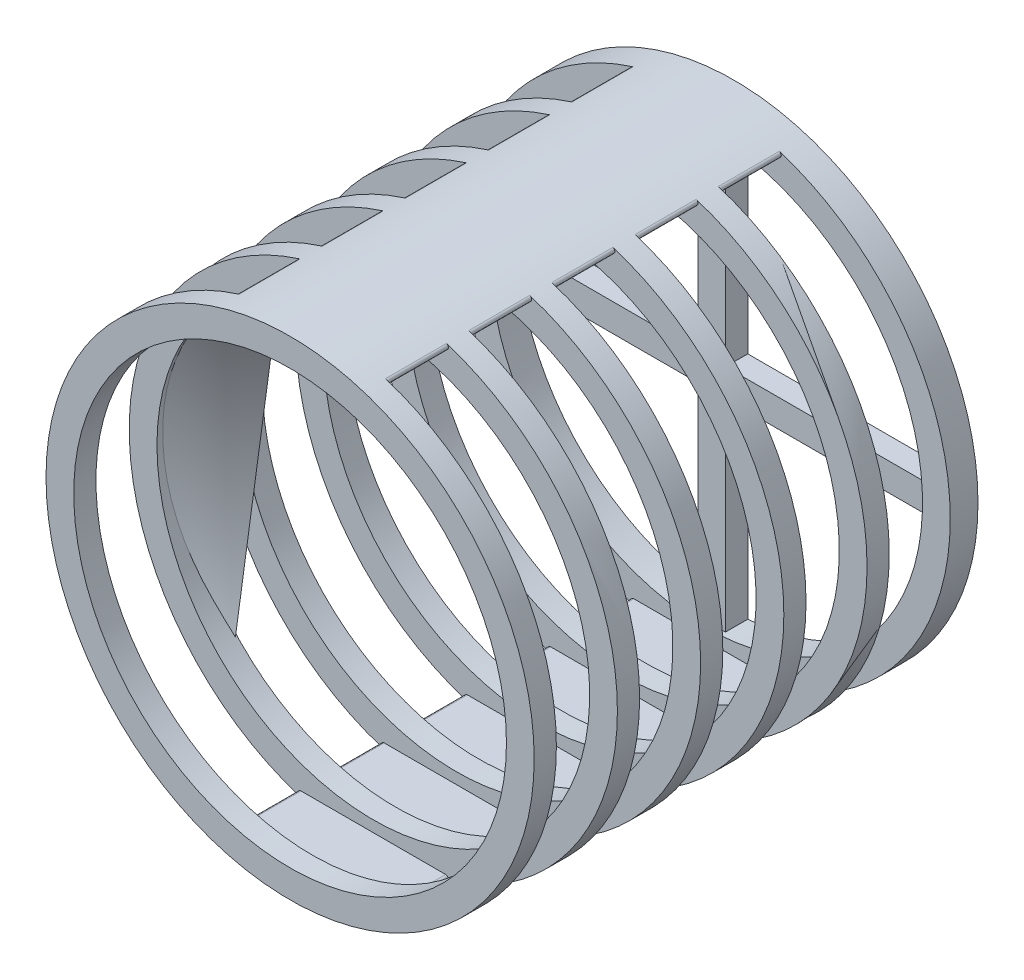
SolidWorks part; units mm, degrees
ref_plane "Plan de face" through (0, 0, 0) normal (0, 0, 1) x (1, 0, 0)
ref_plane "Plan de dessus" through (0, 0, 0) normal (0, 1, 0) x (1, 0, 0)
ref_plane "Plan de droite" through (0, 0, 0) normal (1, 0, 0) x (0, 0, -1)
sketch "Esquisse2" plane through (0, 0, 0) normal (0, 0, 1) x (1, 0, 0)
  circle A0 centre (0, 0) radius 44
  circle A1 centre (0, 0) radius 39
  dimension "D1" = 78
  dimension "D2" = 5
extrude "Boss.-Extru.1" add sketch "Esquisse2" along normal blind 80
sketch "Esquisse3" plane through (0, 0, 0) normal (0, 0, -1) x (-1, 0, 0)
  line L0 (-2.5, 2.5) -> (-42, 2.5)
  line L1 (-42, 2.5) -> (-42, -2.5)
  line L2 (-42, 0) -> (0, 0) construction
  line L3 (-2.5, -2.5) -> (-42, -2.5)
  line L4 (2.5, 2.5) -> (2.5, 42)
  line L5 (2.5, 42) -> (-2.5, 42)
  line L6 (-2.5, 2.5) -> (-2.5, 42)
  line L7 (0, 42) -> (0, 0) construction
  line L8 (2.5, -2.5) -> (42, -2.5)
  line L9 (42, -2.5) -> (42, 2.5)
  line L10 (2.5, 2.5) -> (42, 2.5)
  line L11 (42, 0) -> (0, 0) construction
  line L12 (-2.5, -2.5) -> (-2.5, -42)
  line L13 (-2.5, -42) -> (2.5, -42)
  line L14 (2.5, -2.5) -> (2.5, -42)
  line L15 (0, -42) -> (0, 0) construction
  circle A1 centre (0, 0) radius 44 construction
  point P9 (0, 0)
  point P10 (-2.5, 4.4124)
  point P27 (0, 0)
  dimension "D1" = 5
  dimension "D2" = 42
  dimension "D3" = 4
extrude "Boss.-Extru.2" add sketch "Esquisse3" against normal blind 4
sketch "Esquisse4" plane through (0, 0, 0) normal (1, 0, 0) x (0, 0, -1)
  line L0 (0, -44) -> (0, 44) construction
  line L1 (-16, -41) -> (-5, -41)
  line L2 (-16, -41) -> (-16, 41)
  line L3 (-16, 41) -> (-5, 41)
  line L4 (-5, -41) -> (-5, 41)
  line L5 (-5, 0) -> (0, 0) construction
  line L6 (-31, -41) -> (-20, -41)
  line L7 (-31, -41) -> (-31, 41)
  line L8 (-31, 41) -> (-20, 41)
  line L9 (-20, -41) -> (-20, 41)
  line L10 (-46, -41) -> (-35, -41)
  line L11 (-46, -41) -> (-46, 41)
  line L12 (-46, 41) -> (-35, 41)
  line L13 (-35, -41) -> (-35, 41)
  line L14 (-61, -41) -> (-50, -41)
  line L15 (-61, -41) -> (-61, 41)
  line L16 (-61, 41) -> (-50, 41)
  line L17 (-50, -41) -> (-50, 41)
  line L18 (-76, -41) -> (-65, -41)
  line L19 (-76, -41) -> (-76, 41)
  line L20 (-76, 41) -> (-65, 41)
  line L21 (-65, -41) -> (-65, 41)
  point P9 (-18, -41)
  dimension "D1" = 5
  dimension "D2" = 11
  dimension "D3" = 82
  dimension "D5" = 15
  dimension "D4" = 5
extrude "Enlèv. mat.-Extru.1" cut sketch "Esquisse4" against normal through all both and the other way through all
fillet "Congé1" radius 0.5 20 edges at (-15.9687, 41, 70.5) (15.9687, 41, 70.5) (-15.9687, 41, 55.5) (15.9687, 41, 55.5) (-15.9687, 41, 40.5) (15.9687, 41, 40.5) (-15.9687, 41, 25.5) (15.9687, 41, 25.5) (-15.9687, 41, 10.5) (15.9687, 41, 10.5) (-15.9687, -41, 70.5) (15.9687, -41, 70.5) (-15.9687, -41, 55.5) (15.9687, -41, 55.5) (-15.9687, -41, 40.5) (15.9687, -41, 40.5) (-15.9687, -41, 25.5) (15.9687, -41, 25.5) (-15.9687, -41, 10.5) (15.9687, -41, 10.5)
